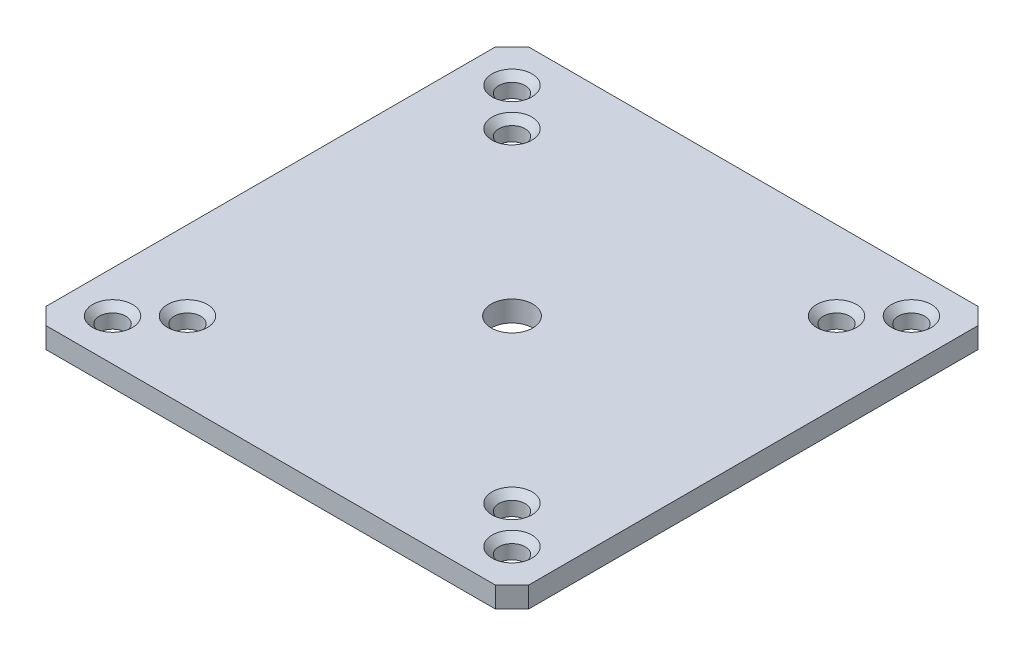
SolidWorks part; units mm, degrees
ref_plane "Front Plane" through (0, 0, 0) normal (0, 0, 1) x (1, 0, 0)
ref_plane "Top Plane" through (0, 0, 0) normal (0, 1, 0) x (1, 0, 0)
ref_plane "Right Plane" through (0, 0, 0) normal (1, 0, 0) x (0, 0, -1)
sketch "Sketch1" plane through (0, 0, 0) normal (0, 1, 0) x (1, 0, 0)
  line L1 (36.83, -36.83) -> (-36.83, -36.83)
  line L2 (36.83, -36.83) -> (36.83, 36.83)
  line L3 (36.83, 36.83) -> (-36.83, 36.83)
  line L4 (-36.83, -36.83) -> (-36.83, 36.83)
  line L5 (36.83, -36.83) -> (-36.83, 36.83) construction
  line L6 (36.83, 36.83) -> (-36.83, -36.83) construction
  circle A0 centre (0, 0) radius 3.175
  point P0 (0, 0)
  point P9 (0, 0)
  dimension "D3" = 6.35
  dimension "D1" = 73.66
  dimension "D2" = 73.66
extrude "Boss-Extrude1" add sketch "Sketch1" along normal blind 3.175
chamfer "Chamfer2" distance 2.54 angle 45 4 edges at (36.83, 1.5875, -36.83) (-36.83, 1.5875, -36.83) (-36.83, 1.5875, 36.83) (36.83, 1.5875, 36.83)
sketch "Sketch2" plane through (0, 3.175, 0) normal (0, 1, 0) x (1, 0, 0)
  line L0 (-1.7463, 0) -> (1.7463, 0) construction
  line L1 (0, -1.7463) -> (0, 1.7463) construction
  point P0 (30.48, 30.48)
  point P1 (-30.48, 30.48)
  point P4 (-30.48, -30.48)
  point P5 (30.48, -30.48)
  dimension "D1" = 60.96
  dimension "D2" = 60.96
  dimension "D3" = 30.48
hole_wizard "#10-32 Tapped Hole1" positions "Sketch2" profile "Sketch3" tap size "#10-32" standard "ANSI Inch" end condition up to next
sketch "Sketch3" plane through (30.48, 3.175, -30.48) normal (1, 0, 0) x (0, 0, 1)
  line L0 (0, 0) -> (0, 3.175)
  line L1 (0, 3.175) -> (2.0193, 3.175)
  line L2 (2.0193, 3.175) -> (2.0193, 1.0287)
  line L3 (2.0193, 1.0287) -> (3.048, 0)
  line L5 (3.048, 0) -> (0, 0)
  line L6 (-2.0193, 1.0287) -> (-3.048, 0) construction
  line L11 (0, -6.35) -> (0, 107.95) construction
  dimension "Thru Tap Drill Dia." = 4.0386
  dimension "Thru Tap Drill Depth" = 3.175
  dimension "Near C'Sink Dia." = 6.096
  dimension "Near C'Sink Angle" = 90
cosmetic thread "Hole Thread1" parameters "D2"=4.826
cosmetic thread "Hole Thread2" parameters "D2"=4.826
cosmetic thread "Hole Thread3" parameters "D2"=4.826
cosmetic thread "Hole Thread4" parameters "D2"=4.826
sketch "Sketch4" plane through (0, 3.175, 0) normal (0, 1, 0) x (1, 0, 0)
  line L0 (-1.7463, 0) -> (1.7463, 0) construction
  line L1 (0, -1.7463) -> (0, 1.7463) construction
  point P0 (-24.765, 24.765)
  point P1 (24.765, 24.765)
  point P4 (-24.765, -24.765)
  point P5 (24.765, -24.765)
  dimension "D1" = 49.53
  dimension "D2" = 49.53
  dimension "D3" = 24.765
hole_wizard "#10-32 Tapped Hole2" positions "Sketch4" profile "Sketch5" tap size "#10-32" standard "ANSI Inch" end condition through all
sketch "Sketch5" plane through (-24.765, 3.175, -24.765) normal (1, 0, 0) x (0, 0, 1)
  line L0 (0, 0) -> (0, 3.175)
  line L1 (0, 3.175) -> (2.0193, 3.175)
  line L2 (2.0193, 3.175) -> (2.0193, 1.0287)
  line L3 (2.0193, 1.0287) -> (3.048, 0)
  line L5 (3.048, 0) -> (0, 0)
  line L6 (-2.0193, 1.0287) -> (-3.048, 0) construction
  line L11 (0, -6.35) -> (0, 107.95) construction
  dimension "Thru Tap Drill Dia." = 4.0386
  dimension "Thru Tap Drill Depth" = 3.175
  dimension "Near C'Sink Dia." = 6.096
  dimension "Near C'Sink Angle" = 90
cosmetic thread "Hole Thread5" parameters "D2"=4.826
cosmetic thread "Hole Thread6" parameters "D2"=4.826
cosmetic thread "Hole Thread7" parameters "D2"=4.826
cosmetic thread "Hole Thread8" parameters "D2"=4.826
